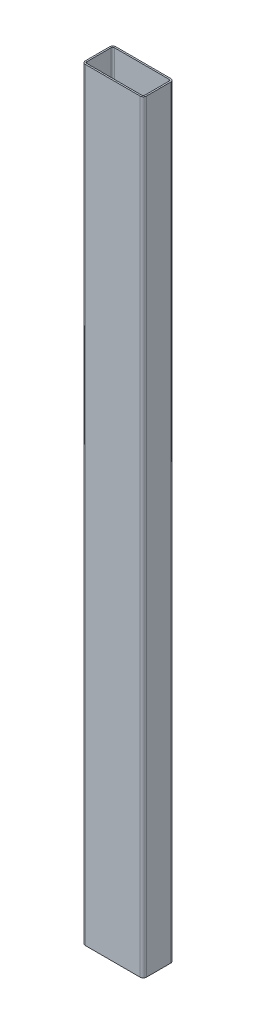
SolidWorks part; units mm, degrees
ref_plane "Front Plane" through (0, 0, 0) normal (0, 0, 1) x (1, 0, 0)
ref_plane "Top Plane" through (0, 0, 0) normal (0, 1, 0) x (1, 0, 0)
ref_plane "Right Plane" through (0, 0, 0) normal (1, 0, 0) x (0, 0, -1)
sketch "Sketch1" plane through (0, 0, 0) normal (0, 1, 0) x (1, 0, 0)
  line L0 (0, 62.0023) -> (0, -67.1111) construction
  line L1 (-58.0545, 0) -> (66.8788, 0) construction
  line L2 (-38, -16) -> (-38, 16)
  line L3 (-36, -20) -> (36, -20)
  line L4 (-40, -16) -> (-40, 16)
  line L5 (-36, 20) -> (36, 20)
  line L6 (40, -16) -> (40, 16)
  line L7 (-40, -20) -> (40, 20) construction
  line L8 (-40, 20) -> (40, -20) construction
  line L9 (-36, 18) -> (36, 18)
  line L10 (38, -16) -> (38, 16)
  line L11 (-36, -18) -> (36, -18)
  arc A0 (-40, -16) -> (-36, -20) centre (-36, -16) ccw
  arc A1 (-40, 16) -> (-36, 20) centre (-36, 16) cw
  arc A2 (36, 20) -> (40, 16) centre (36, 16) cw
  arc A3 (36, -20) -> (40, -16) centre (36, -16) ccw
  arc A4 (-38, 16) -> (-36, 18) centre (-36, 16) cw
  arc A5 (36, 18) -> (38, 16) centre (36, 16) cw
  arc A6 (36, -18) -> (38, -16) centre (36, -16) ccw
  arc A7 (-38, -16) -> (-36, -18) centre (-36, -16) ccw
  point P5 (0, 0)
  dimension "D1" = 4
  dimension "D2" = 80
  dimension "D3" = 40
  dimension "D4" = 2
extrude "Boss-Extrude1" add sketch "Sketch1" along normal mid plane 1000
